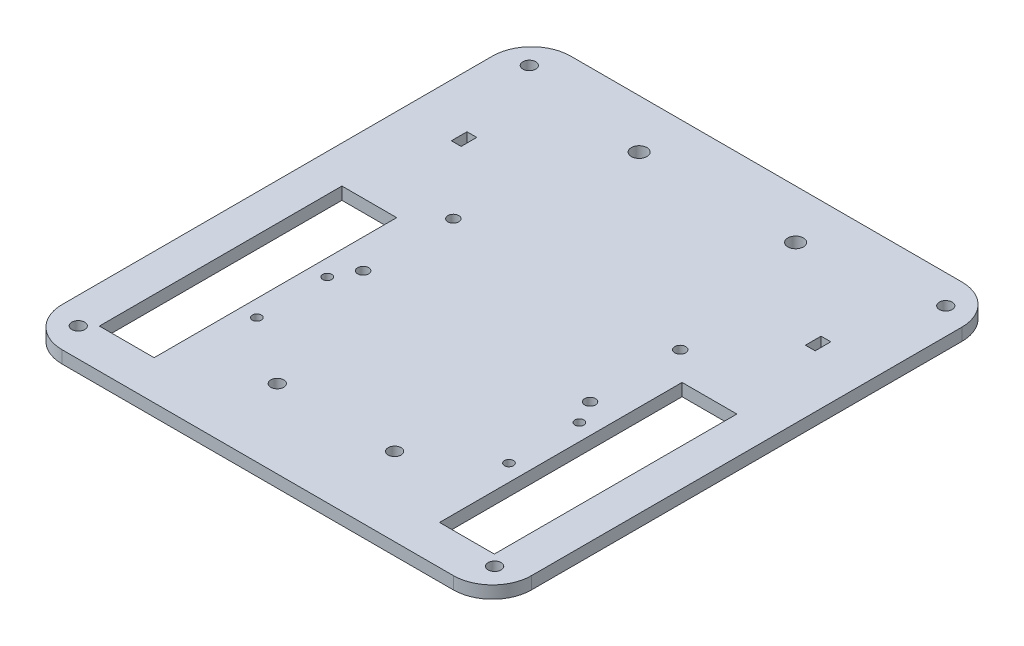
SolidWorks part; units mm, degrees
ref_plane "Front Plane" through (0, 0, 0) normal (0, 0, 1) x (1, 0, 0)
ref_plane "Top Plane" through (0, 0, 0) normal (0, 1, 0) x (1, 0, 0)
ref_plane "Right Plane" through (0, 0, 0) normal (1, 0, 0) x (0, 0, -1)
sketch "Sketch1" plane through (0, 0, 0) normal (0, 1, 0) x (1, 0, 0)
  line L0 (-60, 0) -> (60, 0) construction
  line L1 (-60, 65) -> (60, 65)
  line L2 (-60, 65) -> (-60, -65)
  line L3 (-60, -65) -> (60, -65)
  line L4 (60, 65) -> (60, -65)
  line L5 (-50.475, 7) -> (-50.475, -55)
  line L6 (-36.475, -55) -> (-50.475, -55)
  line L7 (-32.5, 17.5) -> (32.5, 17.5)
  line L8 (-32.5, 17.5) -> (-32.5, -12.5)
  line L9 (-32.5, -12.5) -> (32.5, -12.5)
  line L10 (32.5, 17.5) -> (32.5, -12.5)
  line L11 (0, 65) -> (0, -65) construction
  line L12 (36.475, 7) -> (50.475, 7)
  line L13 (-29, 14) -> (29, 14)
  line L14 (-29, 14) -> (-29, -9.05)
  line L15 (-29, -9.05) -> (29, -9.05)
  line L16 (29, 14) -> (29, -9.05)
  line L17 (36.475, 7) -> (36.475, -55)
  line L18 (36.475, -55) -> (50.475, -55)
  line L19 (50.475, 7) -> (50.475, -55)
  line L20 (-36.475, 7) -> (-36.475, -55)
  line L21 (-36.475, 7) -> (-50.475, 7)
  line L54 (-60, -65) -> (60, 65) construction
  line L55 (-60, 65) -> (60, -65) construction
  line L56 (-44, 31) -> (-46.5, 35) construction
  line L57 (44, 35) -> (46.5, 35)
  line L58 (44, 35) -> (44, 31)
  line L59 (44, 31) -> (46.5, 31)
  line L60 (46.5, 35) -> (46.5, 31)
  line L61 (44, 35) -> (46.5, 31) construction
  line L62 (44, 31) -> (46.5, 35) construction
  line L63 (-44, 35) -> (-46.5, 31) construction
  line L64 (-46.5, 35) -> (-46.5, 31)
  line L65 (-44, 31) -> (-46.5, 31)
  line L66 (-44, 35) -> (-44, 31)
  line L67 (-44, 35) -> (-46.5, 35)
  circle A0 centre (29, 14) radius 1.4
  circle A1 centre (29, -9.05) radius 1.4
  circle A2 centre (-29, -9.05) radius 1.4
  circle A3 centre (-29, 14) radius 1.4
  circle A4 centre (32.225, -15) radius 1.15
  circle A5 centre (32.225, -33) radius 1.15
  circle A6 centre (-32.225, -33) radius 1.15
  circle A7 centre (-32.225, -15) radius 1.15
  circle A8 centre (20, 52.5) radius 2
  circle A9 centre (-20, 52.5) radius 2
  circle A10 centre (53.2172, -57.652) radius 1.65
  circle A11 centre (53.2172, 57.652) radius 1.65
  circle A12 centre (-53.2172, -57.652) radius 1.65
  circle A13 centre (-53.2172, 57.652) radius 1.65
  circle A14 centre (-15, -45) radius 1.65
  circle A15 centre (15, -45) radius 1.65
  point P0 (0, 0)
  point P11 (0, 0)
  point P83 (45.25, 33)
  point P92 (-45.25, 33)
  dimension "D5" = 2.8
  dimension "D6" = 2.3
  dimension "D18" = 4
  dimension "D27" = 3.3
  dimension "D21" = 3.3
  dimension "D1" = 65
  dimension "D2" = 30
  dimension "D3" = 58
  dimension "D4" = 23.05
  dimension "D7" = 18
  dimension "D9" = 4.25
  dimension "D10" = 14
  dimension "D11" = 62
  dimension "D8" = 22
  dimension "D12" = 9.525
  dimension "D13" = 120
  dimension "D14" = 130
  dimension "D16" = 3.5
  dimension "D17" = 3.5
  dimension "D19" = 20
  dimension "D26" = 10
  dimension "D28" = 10
  dimension "D15" = 12.5
  dimension "D29" = 14
  dimension "D32" = 2.5
  dimension "D33" = 4
  dimension "D34" = 44
  dimension "D35" = 30
  dimension "D20" = 15
  dimension "D22" = 20
extrude "Boss-Extrude1" add sketch "Sketch1" along normal blind 3.175 contours L4 L1 L2 L3 A6 A5 A4 L21 L20 L6 L5 L7 L10 L9 L8 L12 L19 L18 L17 A7 | L10 L7 L8 L9 L13 A9 A8 A0 L16 A1 L15 A2 L14 A3 | L13 A9 A3 L14 A2 L15 A1 L16 A0 A8
fillet "Fillet1" radius 10 4 edges at (60, 1.5875, -65) (60, 1.5875, 65) (-60, 1.5875, 65) (-60, 1.5875, -65)
equation "\"D8@Sketch1\"=(\"D11@Sketch1\"-\"D7@Sketch1\")/2"
